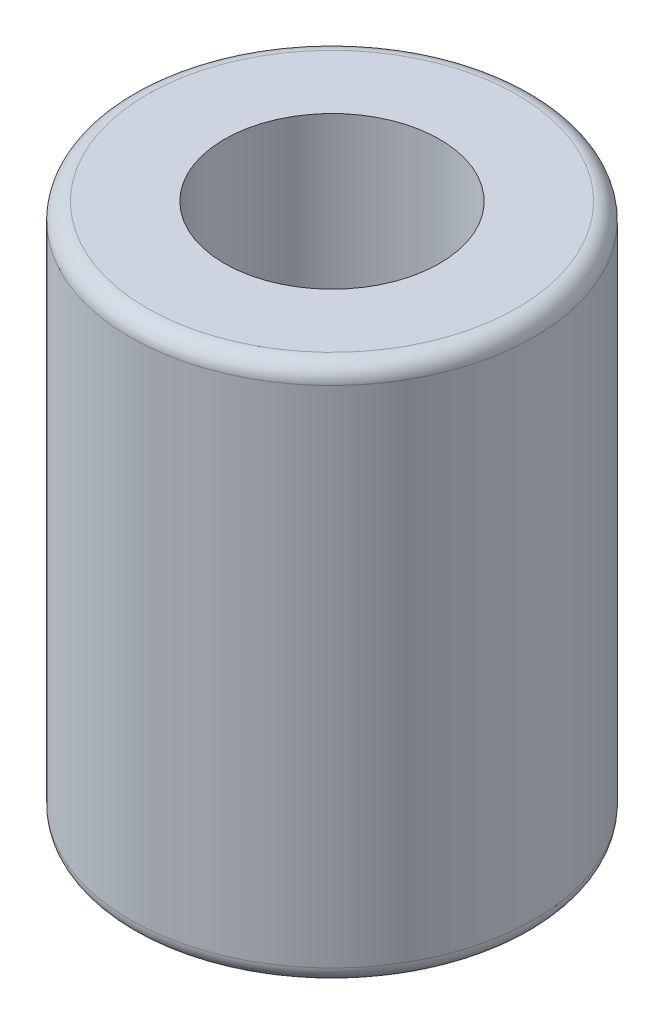
SolidWorks part; units mm, degrees
ref_plane "Front Plane" through (0, 0, 0) normal (0, 0, 1) x (1, 0, 0)
ref_plane "Top Plane" through (0, 0, 0) normal (0, 1, 0) x (1, 0, 0)
ref_plane "Right Plane" through (0, 0, 0) normal (1, 0, 0) x (0, 0, -1)
sketch "Sketch1" plane through (0, 0, 0) normal (0, 1, 0) x (1, 0, 0)
  circle A0 centre (0, 0) radius 3
  circle A1 centre (0, 0) radius 1.6
  dimension "D1" = 3.2
  dimension "D2" = 6
extrude "Boss-Extrude1" add sketch "Sketch1" along normal blind 8
fillet "Fillet1" radius 0.25 2 edges at (0, 0, 3) (0, 8, 3)
